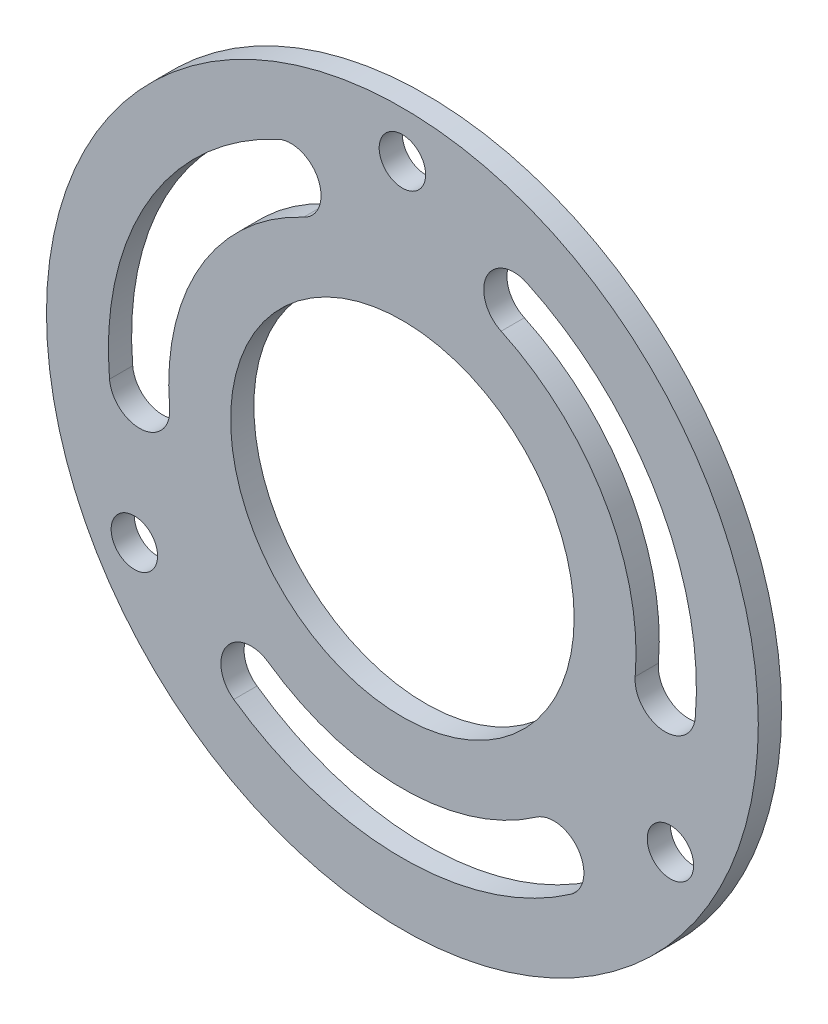
SolidWorks part; units mm, degrees
material "Thornel Mat VMA"
ref_plane "前视基准面" through (0, 0, 0) normal (0, 0, 1) x (1, 0, 0)
ref_plane "上视基准面" through (0, 0, 0) normal (0, 1, 0) x (1, 0, 0)
ref_plane "右视基准面" through (0, 0, 0) normal (1, 0, 0) x (0, 0, -1)
sketch "草图1" plane through (0, 0, 0) normal (0, 0, 1) x (1, 0, 0)
  line L3 (0, 20) -> (0, 0) construction
  circle A0 centre (0, 0) radius 23
  circle A2 centre (0, 20) radius 1.5
  circle A5 centre (0, 0) radius 11.1
  circle A8 centre (0, 0) radius 20 construction
  circle A16 centre (17.3205, -10) radius 1.5
  circle A17 centre (-17.3205, -10) radius 1.5
  point P3 (-7.6978, -21.3717)
  dimension "D1" = 46
  dimension "D4" = 3
  dimension "D7" = 3
  dimension "D6" = 22.2
  dimension "D5" = 40
extrude "凸台-拉伸1" add sketch "草图1" along normal blind 1.5
sketch "草图2" plane through (0, 0, 1.5) normal (0, 0, 1) x (1, 0, 0)
  line L0 (0, 0) -> (-16.9851, -1.486) construction
  line L1 (-7.2056, 15.4525) -> (0, 0) construction
  line L2 (-17.3205, -10) -> (0, 0) construction
  line L3 (0, 0) -> (0, 20) construction
  arc A0 (-7.2056, 15.4525) -> (-16.9851, -1.486) centre (0, 0) ccw construction
  arc A1 (-8.0297, 17.2198) -> (-18.9277, -1.656) centre (0, 0) ccw
  arc A2 (-6.3815, 13.6852) -> (-15.0425, -1.3161) centre (0, 0) ccw
  arc A3 (-6.3815, 13.6852) -> (-8.0297, 17.2198) centre (-7.2056, 15.4525) ccw
  arc A4 (-18.9277, -1.656) -> (-15.0425, -1.3161) centre (-16.9851, -1.486) ccw
  circle A5 centre (0, 0) radius 11.1 construction
  circle A6 centre (0, 0) radius 23 construction
  arc A7 (16.9851, -1.486) -> (7.2056, 15.4525) centre (0, 0) ccw construction
  arc A20 (18.9277, -1.656) -> (8.0297, 17.2198) centre (0, 0) ccw
  arc A21 (15.0425, -1.3161) -> (6.3815, 13.6852) centre (0, 0) ccw
  arc A22 (15.0425, -1.3161) -> (18.9277, -1.656) centre (16.9851, -1.486) ccw
  arc A23 (8.0297, 17.2198) -> (6.3815, 13.6852) centre (7.2056, 15.4525) ccw
  arc A24 (-9.7795, -13.9665) -> (9.7795, -13.9665) centre (0, 0) ccw construction
  arc A25 (-10.898, -15.5639) -> (10.898, -15.5639) centre (0, 0) ccw
  arc A26 (-8.661, -12.3692) -> (8.661, -12.3692) centre (0, 0) ccw
  arc A27 (-8.661, -12.3692) -> (-10.898, -15.5639) centre (-9.7795, -13.9665) ccw
  arc A28 (10.898, -15.5639) -> (8.661, -12.3692) centre (9.7795, -13.9665) ccw
  point P4 (-14.7657, 8.525)
  point P24 (14.7657, 8.525)
  point P32 (0, -17.05)
  dimension "D1" = 4
  dimension "D2" = 4
  dimension "D5" = 3
  dimension "D3" = 25
  dimension "D4" = 25
extrude "切除-拉伸1" cut sketch "草图2" against normal through all
